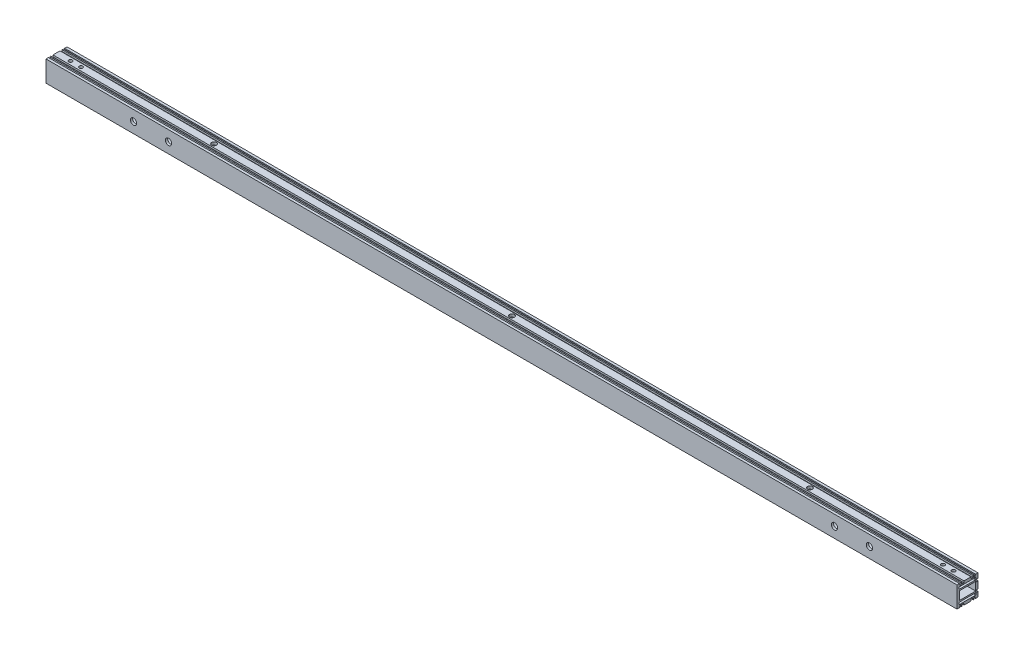
SolidWorks part; units mm, degrees
ref_plane "前视基准面" through (0, 0, 0) normal (0, 0, 1) x (1, 0, 0)
ref_plane "上视基准面" through (0, 0, 0) normal (0, 1, 0) x (1, 0, 0)
ref_plane "右视基准面" through (0, 0, 0) normal (1, 0, 0) x (0, 0, -1)
sketch "草图1" plane through (0, 0, 0) normal (1, 0, 0) x (0, 0, -1)
  line L0 (-15, 15) -> (15, -15) construction
  line L1 (-15, 15) -> (-11.5, 15)
  line L2 (-15, 15) -> (-15, -15)
  line L3 (-15, -15) -> (-11.5, -15)
  line L4 (15, 15) -> (15, 8)
  line L5 (15, 15) -> (-15, -15) construction
  line L6 (-11.5, 15) -> (-11.5, 13.5)
  line L7 (-11.5, 13.5) -> (-11, 13.5)
  line L8 (-11, 13.5) -> (-11, 12)
  line L9 (-11, 12) -> (-9.5, 12)
  line L10 (-9.5, 12) -> (-9.5, 15)
  line L11 (-9.5, 15) -> (-8, 15)
  line L12 (-8, 15) -> (-8, 12.5)
  line L13 (-8, 12.5) -> (-5, 12.5)
  line L14 (-5, 12.5) -> (-5, 15)
  line L15 (-5, 15) -> (5, 15)
  line L16 (0, 21.5201) -> (0, -18.309) construction
  line L17 (0, 55) -> (0, -55) construction
  line L18 (5, 12.5) -> (5, 15)
  line L19 (8, 12.5) -> (5, 12.5)
  line L20 (8, 15) -> (8, 12.5)
  line L21 (9.5, 15) -> (8, 15)
  line L22 (9.5, 12) -> (9.5, 15)
  line L23 (11, 12) -> (9.5, 12)
  line L24 (11, 13.5) -> (11, 12)
  line L25 (11.5, 13.5) -> (11, 13.5)
  line L26 (11.5, 15) -> (11.5, 13.5)
  line L27 (8, 15) -> (9.5, 15)
  line L28 (11.5, 15) -> (15, 15)
  line L29 (-19.8303, 0) -> (22.13, 0) construction
  line L30 (55, 0) -> (-55, 0) construction
  line L31 (8, -15) -> (9.5, -15)
  line L32 (11.5, -15) -> (11.5, -13.5)
  line L33 (11.5, -13.5) -> (11, -13.5)
  line L34 (11, -13.5) -> (11, -12)
  line L35 (11, -12) -> (9.5, -12)
  line L36 (9.5, -12) -> (9.5, -15)
  line L37 (9.5, -15) -> (8, -15)
  line L38 (8, -15) -> (8, -12.5)
  line L39 (8, -12.5) -> (5, -12.5)
  line L40 (5, -12.5) -> (5, -15)
  line L41 (-5, -15) -> (5, -15)
  line L42 (-5, -12.5) -> (-5, -15)
  line L43 (-8, -12.5) -> (-5, -12.5)
  line L44 (-8, -15) -> (-8, -12.5)
  line L45 (-9.5, -15) -> (-8, -15)
  line L46 (-9.5, -12) -> (-9.5, -15)
  line L47 (-11, -12) -> (-9.5, -12)
  line L48 (-11, -13.5) -> (-11, -12)
  line L49 (-11.5, -13.5) -> (-11, -13.5)
  line L50 (-11.5, -15) -> (-11.5, -13.5)
  line L51 (-9.5, -15) -> (-8, -15)
  line L52 (-5, -15) -> (5, -15)
  line L53 (8, -15) -> (9.5, -15)
  line L54 (11.5, -15) -> (15, -15)
  line L55 (15, 8) -> (12.5, 8)
  line L56 (12.5, 8) -> (12.5, 5)
  line L57 (12.5, 5) -> (15, 5)
  line L58 (12.5, -5) -> (15, -5)
  line L59 (12.5, -8) -> (12.5, -5)
  line L60 (15, -8) -> (12.5, -8)
  line L61 (15, 5) -> (15, -5)
  line L62 (15, -8) -> (15, -15)
  line L63 (12, -10.5) -> (12, -8.5)
  line L64 (-11.5, 11) -> (11.5, 11)
  line L65 (-12, 10.5) -> (-12, 8.5)
  line L66 (-11.5, 8) -> (11.5, 8)
  line L67 (12, 10.5) -> (12, 8.5)
  line L68 (-11.5, -8) -> (11.5, -8)
  line L69 (-12, -10.5) -> (-12, -8.5)
  line L70 (-11.5, -11) -> (11.5, -11)
  line L72 (-11.75, 6) -> (11.75, 6)
  line L73 (-11.75, 6) -> (-11.75, -6)
  line L74 (-11.75, -6) -> (11.75, -6)
  line L75 (11.75, 6) -> (11.75, -6)
  arc A0 (12, 8.5) -> (11.5, 8) centre (11.5, 8.5) cw
  arc A1 (11.5, 11) -> (12, 10.5) centre (11.5, 10.5) cw
  arc A2 (-11.5, 11) -> (-12, 10.5) centre (-11.5, 10.5) ccw
  arc A3 (-11.5, 8) -> (-12, 8.5) centre (-11.5, 8.5) cw
  arc A8 (-11.5, -8) -> (-12, -8.5) centre (-11.5, -8.5) ccw
  arc A9 (-11.5, -11) -> (-12, -10.5) centre (-11.5, -10.5) cw
  arc A10 (11.5, -11) -> (12, -10.5) centre (11.5, -10.5) ccw
  arc A11 (12, -8.5) -> (11.5, -8) centre (11.5, -8.5) ccw
  point P69 (12, 11)
  point P72 (-12, 11)
  point P77 (-11, -13.5)
  point P80 (11, -13.5)
  point P83 (11, 13.5)
  point P86 (-11, 13.5)
  point P99 (-12, -11)
  point P100 (12, -11)
  dimension "D17" = 0.5
  dimension "D1" = 3.5
  dimension "D2" = 1.5
  dimension "D3" = 0.5
  dimension "D4" = 1.5
  dimension "D5" = 3
  dimension "D6" = 30
  dimension "D7" = 30
  dimension "D8" = 1.5
  dimension "D9" = 2.5
  dimension "D10" = 3
  dimension "D11" = 2.5
  dimension "D12" = 7
  dimension "D13" = 3
  dimension "D14" = 4
  dimension "D15" = 3
  dimension "D16" = 24
  dimension "D19" = 23.5
  dimension "D20" = 12
extrude "凸台-拉伸1" add sketch "草图1" along normal mid plane 1301
hole_wizard "M6 螺纹孔1" positions "草图3" profile "草图2" tap size "M6" standard "GB"
sketch "草图3" plane through (0, 0, -15) normal (0, 0, -1) x (-1, 0, 0)
  point P0 (-615.5, 0)
  point P3 (-630.5, 0)
  point P6 (630.5, 0)
  point P9 (615.5, 0)
sketch "草图2" plane through (615.5, 0, -15) normal (1, 0, 0) x (0, 1, 0)
  line L0 (0, 0) -> (0, 20.5022)
  line L1 (0, 20.5022) -> (2.5, 19)
  line L2 (2.5, 19) -> (2.5, 0)
  line L5 (2.5, 0) -> (0, 0)
  line L10 (0, 20.5022) -> (-2.5, 19) construction
  line L11 (0, -6.35) -> (0, 107.95) construction
  dimension "螺纹孔钻头直径" = 5
  dimension "螺纹孔钻头深度" = 19
  dimension "导头角度" = 118
cosmetic thread "孔螺蚊线1" parameters "D1"=3.25, "D2"=6
cosmetic thread "孔螺蚊线2" parameters "D1"=3.25, "D2"=6
cosmetic thread "孔螺蚊线3" parameters "D1"=3.25, "D2"=6
cosmetic thread "孔螺蚊线4" parameters "D1"=3.25, "D2"=6
hole_wizard "M6 螺纹孔2" positions "草图5" profile "草图4" tap size "M6" standard "GB"
sketch "草图5" plane through (0, 15, 0) normal (0, 1, 0) x (1, 0, 0)
  point P0 (630.5, 0)
  point P3 (615.5, 0)
  point P6 (-630.5, 0)
  point P9 (-615.5, 0)
sketch "草图4" plane through (630.5, 15, 0) normal (1, 0, 0) x (0, 0, 1)
  line L0 (0, 0) -> (0, 20.5022)
  line L1 (0, 20.5022) -> (2.5, 19)
  line L2 (2.5, 19) -> (2.5, 0)
  line L5 (2.5, 0) -> (0, 0)
  line L10 (0, 20.5022) -> (-2.5, 19) construction
  line L11 (0, -6.35) -> (0, 107.95) construction
  dimension "螺纹孔钻头直径" = 5
  dimension "螺纹孔钻头深度" = 19
  dimension "导头角度" = 118
cosmetic thread "孔螺蚊线5" parameters "D1"=9, "D2"=6
cosmetic thread "孔螺蚊线6" parameters "D1"=9, "D2"=6
cosmetic thread "孔螺蚊线7" parameters "D1"=9, "D2"=6
cosmetic thread "孔螺蚊线8" parameters "D1"=9, "D2"=6
hole_wizard "Ø9.0 (9) 直径孔1" positions "草图8" profile "草图6" hole size "Ø9.0" standard "GB" end condition through all
sketch "草图8" plane through (0, 0, -15) normal (0, 0, -1) x (-1, 0, 0)
  line L0 (-650.5, -15) -> (650.5, -15) construction
  line L1 (650.5, 6) -> (650.5, -6) construction
  line L2 (650.5, 5) -> (650.5, -5) construction
  line L3 (-650.5, -8) -> (-650.5, -15) construction
  point P0 (-525.5, 0)
  point P2 (-475.5, 0)
  point P4 (475.5, 0)
  point P6 (525.5, 0)
  dimension "D1" = 15
  dimension "D2" = 15
  dimension "D3" = 175
  dimension "D4" = 125
  dimension "D5" = 125
  dimension "D6" = 15
  dimension "D7" = 15
  dimension "D8" = 175
sketch "草图6" plane through (525.5, 0, -15) normal (1, 0, 0) x (0, 1, 0)
  line L0 (0, 0) -> (0, 30)
  line L1 (0, 30) -> (4.5, 30)
  line L2 (4.5, 30) -> (4.5, 0)
  line L5 (4.5, 0) -> (0, 0)
  line L11 (0, -6.35) -> (0, 107.95) construction
  dimension "通孔孔直径" = 9
  dimension "通孔孔深度" = 30
hole_wizard "M6 螺纹孔3" positions "草图10" profile "草图9" tap size "M6" standard "GB"
sketch "草图10" plane through (0, -15, 0) normal (0, -1, 0) x (-1, 0, 0)
  line L0 (-650.5, 15) -> (650.5, 15) construction
  line L1 (-650.5, -5) -> (-650.5, 5) construction
  line L2 (650.5, -5) -> (650.5, 5) construction
  point P0 (-425.5, 0)
  point P2 (0, 0)
  point P4 (425.5, 0)
  dimension "D1" = 15
  dimension "D2" = 225
  dimension "D3" = 650.5
  dimension "D4" = 225
  dimension "D5" = 15
  dimension "D6" = 15
sketch "草图9" plane through (425.5, -15, 0) normal (1, 0, 0) x (0, 0, -1)
  line L0 (0, 0) -> (0, 16.5022)
  line L1 (0, 16.5022) -> (2.5, 15)
  line L2 (2.5, 15) -> (2.5, 0)
  line L5 (2.5, 0) -> (0, 0)
  line L10 (0, 16.5022) -> (-2.5, 15) construction
  line L11 (0, -6.35) -> (0, 107.95) construction
  dimension "螺纹孔钻头直径" = 5
  dimension "螺纹孔钻头深度" = 15
  dimension "导头角度" = 118
cosmetic thread "孔螺蚊线9" parameters "D1"=9, "D2"=6
cosmetic thread "孔螺蚊线10" parameters "D1"=9, "D2"=6
cosmetic thread "孔螺蚊线11" parameters "D1"=9, "D2"=6
hole_wizard "Ø7.0 (7) 直径孔1" positions "草图12" profile "草图11" hole size "Ø7.0" standard "GB"
sketch "草图12" plane through (0, 15, 0) normal (0, 1, 0) x (1, 0, 0)
  line L0 (650.5, -15) -> (-650.5, -15) construction
  line L1 (650.5, -5) -> (650.5, 5) construction
  line L3 (-650.5, -5) -> (-650.5, 5) construction
  point P0 (-425.5, 0)
  point P2 (0, 0)
  point P4 (425.5, 0)
  dimension "D1" = 15
  dimension "D2" = 225
  dimension "D3" = 650.5
  dimension "D4" = 15
  dimension "D5" = 15
  dimension "D6" = 225
sketch "草图11" plane through (-425.5, 15, 0) normal (1, 0, 0) x (0, 0, 1)
  line L0 (0, 0) -> (0, 17.103)
  line L1 (0, 17.103) -> (3.5, 15)
  line L2 (3.5, 15) -> (3.5, 0)
  line L5 (3.5, 0) -> (0, 0)
  line L10 (0, 17.103) -> (-3.5, 15) construction
  line L11 (0, -6.35) -> (0, 107.95) construction
  dimension "孔直径" = 7
  dimension "孔深度" = 15
  dimension "导头角度" = 118
